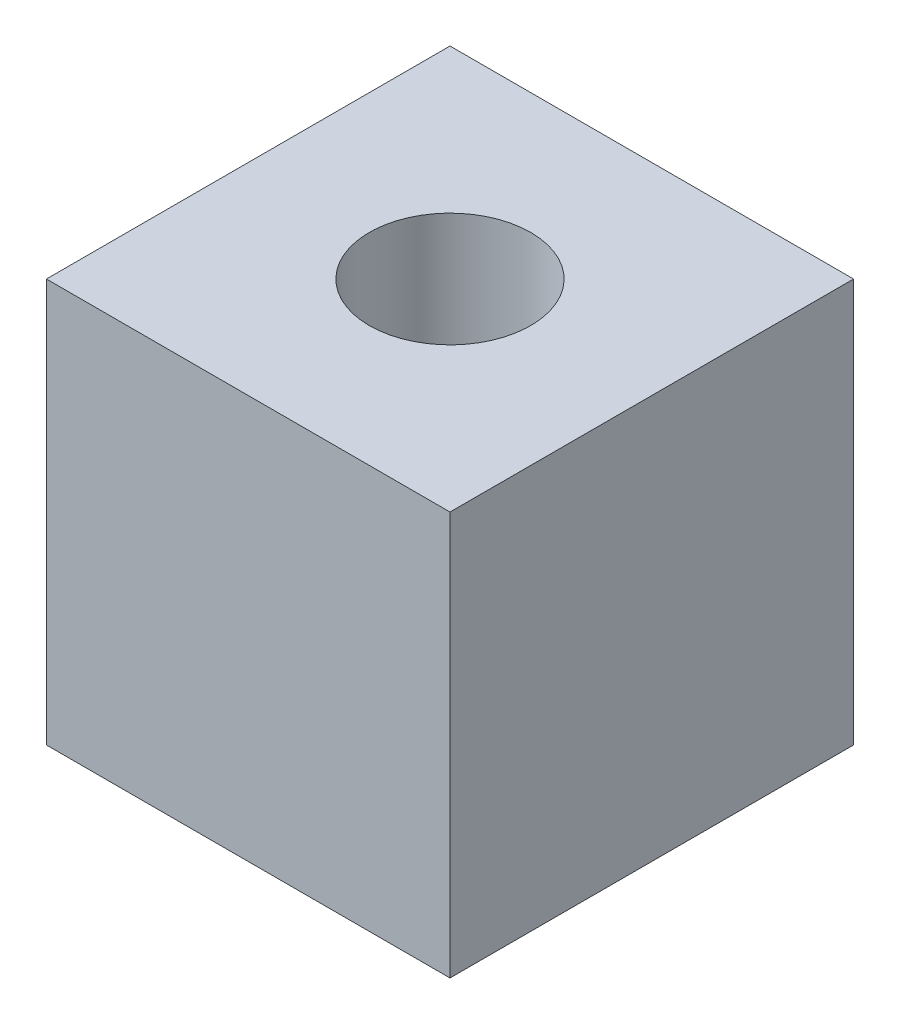
SolidWorks part; units mm, degrees
ref_plane "Front Plane" through (0, 0, 0) normal (0, 0, 1) x (1, 0, 0)
ref_plane "Top Plane" through (0, 0, 0) normal (0, 1, 0) x (1, 0, 0)
ref_plane "Right Plane" through (0, 0, 0) normal (1, 0, 0) x (0, 0, -1)
sketch "Sketch1" plane through (0, 0, 0) normal (0, 1, 0) x (1, 0, 0)
  line L1 (-25, 25) -> (25, 25)
  line L2 (-25, 25) -> (-25, -25)
  line L3 (-25, -25) -> (25, -25)
  line L4 (25, 25) -> (25, -25)
  line L5 (-25, 25) -> (25, -25) construction
  line L6 (-25, -25) -> (25, 25) construction
  circle A0 centre (0, 0) radius 10
  point P0 (0, 0)
  dimension "D3" = 20
  dimension "D1" = 50
  dimension "D2" = 50
extrude "Boss-Extrude1" add sketch "Sketch1" along normal blind 50
